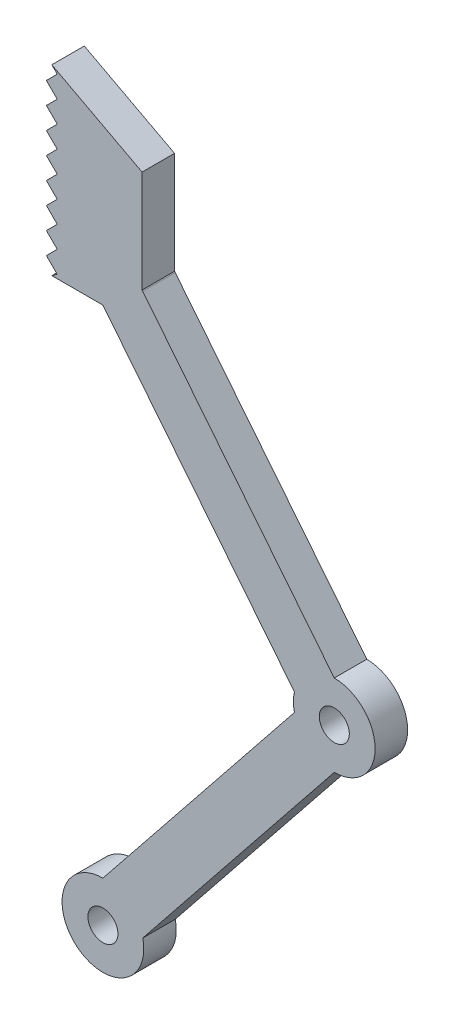
SolidWorks part; units mm, degrees
ref_plane "Front Plane" through (0, 0, 0) normal (0, 0, 1) x (1, 0, 0)
ref_plane "Top Plane" through (0, 0, 0) normal (0, 1, 0) x (1, 0, 0)
ref_plane "Right Plane" through (0, 0, 0) normal (1, 0, 0) x (0, 0, -1)
sketch "Sketch1" plane through (0, 0, 0) normal (0, 0, 1) x (1, 0, 0)
  line L0 (0, 0) -> (0, 4) construction
  line L1 (0, 4) -> (3.9031, 0.875) construction
  line L2 (0, 0) -> (1.9516, 2.4375) construction
  line L3 (1.9516, 2.4375) -> (22.6531, 28.2937) construction
  line L4 (0, 4) -> (18.75, 27.4187)
  line L5 (3.9031, 0.875) -> (22.6531, 24.2937)
  line L11 (18.7498, 29.168) -> (-0.0046, 52.5832)
  line L12 (22.6524, 32.2937) -> (3.8979, 55.7089)
  line L13 (18.7498, 29.168) -> (22.6524, 32.2937) construction
  line L14 (22.6531, 28.2937) -> (20.7011, 30.7309) construction
  line L15 (20.7011, 30.7309) -> (21.7634, 29.4045) construction
  line L19 (-5.0046, 2.4908) -> (-4.8942, -57.5091) construction
  line L20 (-12.5046, 2.477) -> (2.4954, 2.5046) construction
  line L21 (-29.8941, -57.5551) -> (20.1058, -57.4631) construction
  line L22 (-5.0046, 2.4908) -> (-5.0046, 52.5832) construction
  line L27 (3.8979, 55.7089) -> (3.832, 55.7841)
  line L32 (-0.0046, 52.5832) -> (-5.0046, 52.5832)
  line L34 (3.832, 65.7841) -> (3.832, 55.7841)
  line L55 (-5.0046, 52.5832) -> (-5.0046, 92.5832) construction
  line L56 (-5.0046, 52.5832) -> (-4.4743, 52.961)
  line L57 (-4.4743, 52.961) -> (-5.5349, 54.0216)
  line L58 (-5.5349, 54.0216) -> (-4.4743, 55.0823)
  line L59 (-4.4743, 55.0823) -> (-5.5349, 56.143)
  line L60 (-5.5349, 56.143) -> (-4.4743, 57.2036)
  line L61 (-4.4743, 57.2036) -> (-5.5349, 58.2643)
  line L62 (-5.5349, 58.2643) -> (-4.4743, 59.325)
  line L63 (-4.4743, 59.325) -> (-5.5349, 60.3856)
  line L64 (-5.5349, 60.3856) -> (-4.4743, 61.4463)
  line L65 (-4.4743, 61.4463) -> (-5.5349, 62.5069)
  line L66 (-5.5349, 62.5069) -> (-4.4743, 63.5676)
  line L67 (-4.4743, 63.5676) -> (-5.5349, 64.6283)
  line L76 (3.832, 65.7841) -> (-5.0046, 70.4655)
  line L77 (-5.5349, 64.6283) -> (-4.4743, 65.6889)
  line L78 (-4.4743, 65.6889) -> (-5.5349, 66.7496)
  line L79 (-5.5349, 66.7496) -> (-4.4743, 67.8102)
  line L80 (-4.4743, 67.8102) -> (-5.5349, 68.8709)
  line L81 (-5.5349, 68.8709) -> (-4.4743, 69.9316)
  line L82 (-4.4743, 69.9316) -> (-5.0046, 70.4655)
  arc A0 (0, 4) -> (3.9031, 0.875) centre (0, 0) ccw
  arc A1 (22.6531, 24.2937) -> (22.6524, 32.2937) centre (22.6531, 28.2937) ccw
  arc A2 (18.75, 27.4187) -> (18.7498, 29.168) centre (22.6531, 28.2937) cw
  dimension "D1" = 4
  dimension "D4" = 4
  dimension "D5" = 5
  dimension "D7" = 30
  dimension "D6" = 10
  dimension "D2" = 5
  dimension "D3" = 30
  dimension "D8" = 0.1
  dimension "D9" = 5
  dimension "D10" = 40
  dimension "D11" = 35.465
  dimension "D12" = 1.5
  dimension "D13" = 10
  dimension "D14" = 0
  dimension "D15" = 1.5
  dimension "D16" = 1.5
  dimension "D17" = 1.5
  dimension "D18" = 0.5303
  dimension "D19" = 0.3778
extrude "Boss-Extrude1" add sketch "Sketch1" along normal blind 3.18
sketch "Sketch2" plane through (0, 0, 0) normal (0, 0, -1) x (-1, 0, 0)
  circle A0 centre (-22.6531, 28.2937) radius 1.47
  dimension "D1" = 2.94
extrude "Cut-Extrude1" cut sketch "Sketch2" against normal through all
sketch "Sketch3" plane through (0, 0, 0) normal (0, 0, -1) x (-1, 0, 0)
  circle A0 centre (0, 0) radius 1.47
  dimension "D1" = 2.94
extrude "Cut-Extrude2" cut sketch "Sketch3" against normal through all
